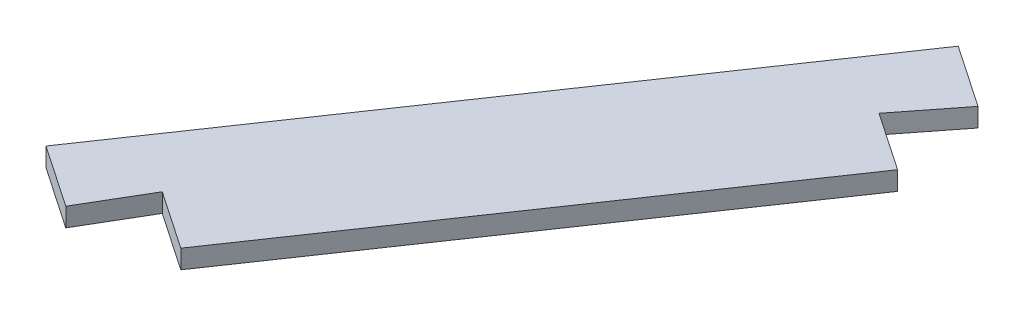
SolidWorks part; units mm, degrees
ref_plane "Front Plane" through (0, 0, 0) normal (0, 0, 1) x (1, 0, 0)
ref_plane "Top Plane" through (0, 0, 0) normal (0, 1, 0) x (1, 0, 0)
ref_plane "Right Plane" through (0, 0, 0) normal (1, 0, 0) x (0, 0, -1)
sketch "Sketch1" plane through (0, 0, 0) normal (0, 1, 0) x (1, 0, 0)
  line L0 (84.8528, 0) -> (0, 84.8528) construction
  line L1 (35.5241, 110.9516) -> (214.4328, 242.3919)
  line L2 (42.4264, 42.4264) -> (226.2742, 226.2742) construction
  line L3 (242.3919, 214.4328) -> (110.9516, 35.5241)
  line L4 (0, 84.8528) -> (0, 0) construction
  line L5 (0, 0) -> (84.8528, 0) construction
  line L6 (42.4264, 42.4264) -> (0, 0) construction
  line L7 (232.7742, 226.2742) -> (226.2742, 219.7742) construction
  line L8 (232.7742, 226.2742) -> (226.2742, 232.7742) construction
  line L9 (226.2742, 219.7742) -> (219.7742, 226.2742) construction
  line L10 (226.2742, 232.7742) -> (219.7742, 226.2742) construction
  line L11 (232.7742, 226.2742) -> (219.7742, 226.2742) construction
  line L12 (226.2742, 219.7742) -> (226.2742, 232.7742) construction
  line L13 (239.2742, 226.2742) -> (226.2742, 213.2742) construction
  line L14 (239.2742, 226.2742) -> (226.2742, 239.2742) construction
  line L15 (226.2742, 213.2742) -> (213.2742, 226.2742) construction
  line L16 (226.2742, 239.2742) -> (213.2742, 226.2742) construction
  line L17 (239.2742, 226.2742) -> (213.2742, 226.2742) construction
  line L18 (226.2742, 213.2742) -> (226.2742, 239.2742) construction
  line L19 (208.5965, 187.3833) -> (187.3833, 208.5965) construction
  line L20 (0, 0) -> (200, 0) construction
  line L21 (214.4328, -242.3919) -> (35.5241, -110.9516)
  line L22 (110.9516, -35.5241) -> (242.3919, -214.4328)
  line L23 (-242.3919, -214.4328) -> (-110.9516, -35.5241)
  line L24 (-35.5241, -110.9516) -> (-214.4328, -242.3919)
  line L25 (-214.4328, 242.3919) -> (-35.5241, 110.9516)
  line L26 (-110.9516, 35.5241) -> (-242.3919, 214.4328)
  line L27 (187.3833, 208.5965) -> (56.5685, 77.7817) construction
  line L28 (-246.2742, 246.2742) -> (246.2742, 246.2742) construction
  line L29 (-246.2742, 246.2742) -> (-246.2742, -246.2742) construction
  line L30 (-246.2742, -246.2742) -> (246.2742, -246.2742) construction
  line L31 (246.2742, 246.2742) -> (246.2742, -246.2742) construction
  line L32 (-246.2742, 246.2742) -> (246.2742, -246.2742) construction
  line L33 (-246.2742, -246.2742) -> (246.2742, 246.2742) construction
  arc A0 (214.4328, 242.3919) -> (242.3919, 214.4328) centre (226.2742, 226.2742) cw
  circle A1 centre (213.2742, 226.2742) radius 1
  circle A2 centre (226.2742, 239.2742) radius 1
  circle A3 centre (239.2742, 226.2742) radius 1
  circle A4 centre (232.7742, 226.2742) radius 2
  circle A5 centre (226.2742, 232.7742) radius 2
  circle A6 centre (219.7742, 226.2742) radius 2
  circle A7 centre (226.2742, 219.7742) radius 2
  circle A8 centre (226.2742, 213.2742) radius 1
  circle A9 centre (187.3833, 208.5965) radius 2
  circle A10 centre (208.5965, 187.3833) radius 2
  arc A11 (242.3919, -214.4328) -> (214.4328, -242.3919) centre (226.2742, -226.2742) cw
  circle A12 centre (226.2742, -239.2742) radius 1
  circle A13 centre (226.2742, -232.7742) radius 2
  circle A14 centre (232.7742, -226.2742) radius 2
  circle A15 centre (239.2742, -226.2742) radius 1
  circle A16 centre (226.2742, -219.7742) radius 2
  circle A17 centre (219.7742, -226.2742) radius 2
  circle A18 centre (213.2742, -226.2742) radius 1
  circle A19 centre (226.2742, -213.2742) radius 1
  circle A20 centre (187.3833, -208.5965) radius 2
  circle A21 centre (208.5965, -187.3833) radius 2
  arc A22 (-214.4328, -242.3919) -> (-242.3919, -214.4328) centre (-226.2742, -226.2742) cw
  circle A23 centre (-239.2742, -226.2742) radius 1
  circle A24 centre (-232.7742, -226.2742) radius 2
  circle A25 centre (-226.2742, -232.7742) radius 2
  circle A26 centre (-226.2742, -239.2742) radius 1
  circle A27 centre (-219.7742, -226.2742) radius 2
  circle A28 centre (-226.2742, -219.7742) radius 2
  circle A29 centre (-226.2742, -213.2742) radius 1
  circle A30 centre (-213.2742, -226.2742) radius 1
  circle A31 centre (-208.5965, -187.3833) radius 2
  circle A32 centre (-187.3833, -208.5965) radius 2
  arc A33 (-242.3919, 214.4328) -> (-214.4328, 242.3919) centre (-226.2742, 226.2742) cw
  circle A34 centre (-226.2742, 239.2742) radius 1
  circle A35 centre (-226.2742, 232.7742) radius 2
  circle A36 centre (-232.7742, 226.2742) radius 2
  circle A37 centre (-239.2742, 226.2742) radius 1
  circle A38 centre (-226.2742, 219.7742) radius 2
  circle A39 centre (-219.7742, 226.2742) radius 2
  circle A40 centre (-213.2742, 226.2742) radius 1
  circle A41 centre (-226.2742, 213.2742) radius 1
  circle A42 centre (-187.3833, 208.5965) radius 2
  circle A43 centre (-208.5965, 187.3833) radius 2
  arc A44 (-110.9516, -35.5241) -> (-110.9516, 35.5241) centre (-159.3049, 0) ccw
  arc A45 (35.5241, -110.9516) -> (-35.5241, -110.9516) centre (0, -159.3049) ccw
  arc A46 (110.9516, -35.5241) -> (110.9516, 35.5241) centre (159.3049, 0) cw
  arc A47 (-35.5241, 110.9516) -> (35.5241, 110.9516) centre (0, 159.3049) ccw
  circle A48 centre (0, 0) radius 96.1769 construction
  point P28 (197.9899, 197.9899)
  point P108 (0, 0)
  dimension "D3" = 20
  dimension "D7" = 2
  dimension "D8" = 2
  dimension "D9" = 4
  dimension "D10" = 4
  dimension "D11" = 4
  dimension "D12" = 2
  dimension "D13" = 4
  dimension "D14" = 2
  dimension "D15" = 4
  dimension "D16" = 4
  dimension "D22" = 60
  dimension "D24" = 192.3538
  dimension "D1" = 260
  dimension "D2" = 120
  dimension "D4" = 60
  dimension "D5" = 26
  dimension "D6" = 13
  dimension "D17" = 30
  dimension "D18" = 40
  dimension "D19" = 200
  dimension "D20" = 45
  dimension "D23" = 185
  dimension "D21" = 4
sketch "Sketch2" plane through (0, 0, 0) normal (0, 1, 0) x (1, 0, 0)
  line L0 (78.5365, -14.2236) -> (78.5012, -26.2236) construction
  line L1 (78.5012, -26.2236) -> (12.8814, 21.2788) construction
  line L2 (12.8814, 21.2788) -> (12.8814, 48.0179) construction
  line L3 (12.8814, 48.0179) -> (-38.4858, 16.8899) construction
  line L4 (-38.4858, 16.8899) -> (-37.5695, 62.8272) construction
  line L5 (-37.5695, 62.8272) -> (12.8814, 21.2788) construction
  line L6 (12.8814, 21.2788) -> (-38.4858, 16.8899) construction
  line L7 (-38.4858, 16.8899) -> (-73.2421, 49.4521) construction
  line L8 (-73.2421, 49.4521) -> (-37.5695, 62.8272) construction
  line L9 (-37.5695, 62.8272) -> (12.8814, 48.0179) construction
  line L10 (12.8814, 48.0179) -> (78.5365, -14.2236) construction
  line L11 (-66.7313, 7.059) -> (-66.7313, -31.9732) construction
  line L12 (-66.7313, 11.059) -> (-31.7313, 11.059)
  line L13 (-66.7313, 11.059) -> (-66.7313, 7.059)
  line L14 (-66.7313, 7.059) -> (-31.7313, 7.059)
  line L15 (-31.7313, 11.059) -> (-31.7313, 7.059)
  line L16 (43.2687, 11.059) -> (8.2687, 11.059)
  line L17 (43.2687, 11.059) -> (43.2687, 7.059)
  line L18 (43.2687, 7.059) -> (8.2687, 7.059)
  line L19 (8.2687, 11.059) -> (8.2687, 7.059)
  line L20 (-66.7313, -31.9732) -> (-31.7313, -31.9732)
  line L21 (-66.7313, -31.9732) -> (-66.7313, -35.9732)
  line L22 (-66.7313, -35.9732) -> (-31.7313, -35.9732)
  line L23 (-31.7313, -31.9732) -> (-31.7313, -35.9732)
  line L24 (8.2687, -31.9732) -> (43.2687, -31.9732)
  line L25 (8.2687, -31.9732) -> (8.2687, -35.9732)
  line L26 (8.2687, -35.9732) -> (43.2687, -35.9732)
  line L27 (43.2687, -31.9732) -> (43.2687, -35.9732)
  line L28 (8.2687, -31.9732) -> (8.2687, 7.059) construction
  line L29 (-31.7313, 7.059) -> (8.2687, 7.059) construction
  line L30 (-31.7313, -31.9732) -> (8.2687, -31.9732) construction
  line L31 (-73.2421, 49.4521) -> (-73.2421, 19.4521) construction
  circle A0 centre (78.5365, -14.2236) radius 1.5
  circle A1 centre (78.5012, -26.2236) radius 1.5
  circle A2 centre (12.8814, 21.2788) radius 1.8
  circle A3 centre (12.8814, 48.0179) radius 1.8
  circle A4 centre (-38.4858, 16.8899) radius 1.8
  circle A5 centre (-37.5695, 62.8272) radius 1.8
  circle A6 centre (-73.2421, 49.4521) radius 1.8
  circle A7 centre (-6.3066, 9.5674) radius 1.8
  circle A8 centre (-73.2421, 19.4521) radius 1.8
  dimension "D1" = 3
  dimension "D2" = 3
  dimension "D3" = 12
  dimension "D5" = 3.6
  dimension "D6" = 3.6
  dimension "D7" = 3.6
  dimension "D8" = 3.6
  dimension "D9" = 3.6
  dimension "D14" = 3.6
  dimension "D29" = 3.6
  dimension "D4" = 4.3889
  dimension "D10" = 51.3673
  dimension "D11" = 26.7391
  dimension "D12" = 50.451
  dimension "D13" = 14.8093
  dimension "D15" = 35
  dimension "D16" = 35
  dimension "D17" = 35
  dimension "D18" = 65.6197
  dimension "D19" = 47.5024
  dimension "D20" = 62.2416
  dimension "D21" = 65.6551
  dimension "D22" = 35
  dimension "D23" = 39.0322
  dimension "D24" = 4
  dimension "D25" = 4
  dimension "D26" = 4
  dimension "D27" = 4
  dimension "D28" = 40
  dimension "D30" = 30
sketch "Sketch4" plane through (0, 0, 0) normal (0, 1, 0) x (1, 0, 0)
  line L0 (139.5103, -2.93) -> (114.7166, 13.96) construction
  line L1 (139.5103, -2.93) -> (201.4404, 87.9801)
  line L2 (114.7166, 13.96) -> (176.6467, 104.8702)
  line L3 (201.4404, 87.9801) -> (176.6467, 104.8702) construction
  line L4 (176.6467, 104.8702) -> (185.0918, 117.267)
  line L5 (185.0918, 117.267) -> (198.3151, 108.259)
  line L6 (198.3151, 108.259) -> (189.0436, 96.4252)
  line L7 (189.0436, 96.4252) -> (201.4404, 87.9801)
  line L8 (114.7166, 13.96) -> (106.2716, 1.5631)
  line L9 (106.2716, 1.5631) -> (119.4949, -7.4449)
  line L10 (119.4949, -7.4449) -> (127.1135, 5.515)
  line L11 (127.1135, 5.515) -> (139.5103, -2.93)
  dimension "D1" = 110
  dimension "D2" = 30
  dimension "D3" = 16
  dimension "D4" = 15
  dimension "D5" = 15
  dimension "D6" = 15
  dimension "D7" = 15
  dimension "D8" = 16
  dimension "D9" = 15
extrude "Boss-Extrude1" add sketch "Sketch4" along normal blind 4
equation "\"D4@Sketch1\"=\"D2@Sketch1\"/2"
equation "\"D8@Sketch1\"=\"D7@Sketch1\""
equation "\"D9@Sketch1\"=\"D10@Sketch1\""
equation "\"D11@Sketch1\"=\"D10@Sketch1\""
equation "\"D12@Sketch1\"=\"D7@Sketch1\""
equation "\"D13@Sketch1\"=\"D10@Sketch1\""
equation "\"D14@Sketch1\"=\"D7@Sketch1\""
